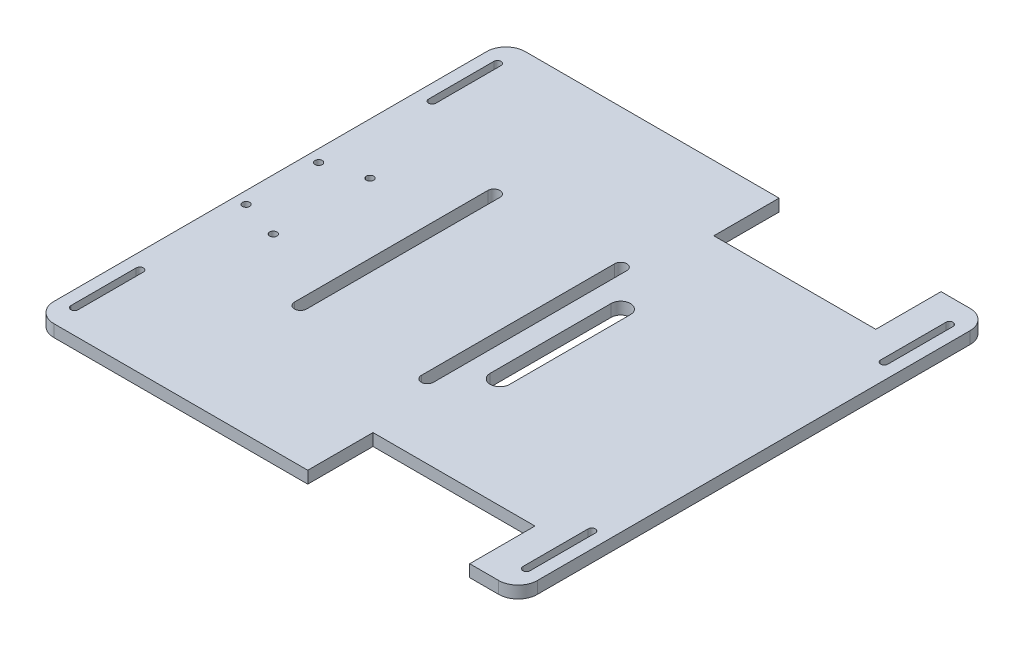
SolidWorks part; units mm, degrees
ref_plane "Front Plane" through (0, 0, 0) normal (0, 0, 1) x (1, 0, 0)
ref_plane "Top Plane" through (0, 0, 0) normal (0, 1, 0) x (1, 0, 0)
ref_plane "Right Plane" through (0, 0, 0) normal (1, 0, 0) x (0, 0, -1)
sketch "Sketch2" plane through (0, 0, 0) normal (0, 1, 0) x (1, 0, 0)
  line L1 (-100, -97.5) -> (100, -97.5)
  line L2 (-100, -97.5) -> (-100, 97.5)
  line L3 (-100, 97.5) -> (100, 97.5)
  line L4 (100, -97.5) -> (100, 97.5)
  line L5 (-100, -97.5) -> (100, 97.5) construction
  line L6 (-100, 97.5) -> (100, -97.5) construction
  point P0 (0, 0)
  dimension "D1" = 200
  dimension "D2" = 195
extrude "Boss-Extrude1" add sketch "Sketch2" along normal blind 5
sketch "Sketch3" plane through (0, 5, 0) normal (0, 1, 0) x (1, 0, 0)
  line L0 (-100, 0) -> (100, 0) construction
  line L1 (-100, 97.5) -> (-100, -97.5) construction
  line L2 (100, -97.5) -> (100, 97.5) construction
  line L3 (0, -97.5) -> (0, 97.5) construction
  line L4 (-100, -97.5) -> (100, -97.5) construction
  line L5 (100, 97.5) -> (-100, 97.5) construction
  line L6 (-93.5, -87.5) -> (-93.5, -60.5) construction
  line L7 (-95, -87.5) -> (-95, -60.5)
  line L8 (-92, -87.5) -> (-92, -60.5)
  line L9 (-93.5, 87.5) -> (-93.5, 60.5) construction
  line L10 (-95, 87.5) -> (-95, 60.5)
  line L11 (-92, 87.5) -> (-92, 60.5)
  line L12 (93.5, 87.5) -> (93.5, 60.5) construction
  line L13 (95, 87.5) -> (95, 60.5)
  line L14 (92, 87.5) -> (92, 60.5)
  line L15 (93.5, -87.5) -> (93.5, -60.5) construction
  line L16 (95, -87.5) -> (95, -60.5)
  line L17 (92, -87.5) -> (92, -60.5)
  arc A0 (-95, -87.5) -> (-92, -87.5) centre (-93.5, -87.5) ccw
  arc A1 (-92, -60.5) -> (-95, -60.5) centre (-93.5, -60.5) ccw
  arc A2 (-95, 87.5) -> (-92, 87.5) centre (-93.5, 87.5) cw
  arc A3 (-92, 60.5) -> (-95, 60.5) centre (-93.5, 60.5) cw
  arc A4 (95, 87.5) -> (92, 87.5) centre (93.5, 87.5) ccw
  arc A5 (92, 60.5) -> (95, 60.5) centre (93.5, 60.5) ccw
  arc A6 (95, -87.5) -> (92, -87.5) centre (93.5, -87.5) cw
  arc A7 (92, -60.5) -> (95, -60.5) centre (93.5, -60.5) cw
  point P14 (-93.5, -74)
  point P21 (-93.5, 74)
  point P28 (93.5, 74)
  point P35 (93.5, -74)
  dimension "D2" = 1.5
  dimension "D3" = 5
  dimension "D4" = 10
  dimension "D1" = 27
extrude "Cut-Extrude1" cut sketch "Sketch3" against normal through all
sketch "Sketch4" plane through (0, 0, 0) normal (0, -1, 0) x (1, 0, 0)
  line L0 (-100, 0) -> (100, 0) construction
  line L1 (-100, -97.5) -> (-100, 97.5) construction
  line L2 (100, 97.5) -> (100, -97.5) construction
  line L3 (100, -97.5) -> (-100, -97.5) construction
  line L4 (13, -97.5) -> (80, -97.5)
  line L5 (13, -97.5) -> (13, -70.5)
  line L6 (13, -70.5) -> (80, -70.5)
  line L7 (80, -97.5) -> (80, -70.5)
  line L8 (80, 97.5) -> (80, 70.5)
  line L9 (13, 97.5) -> (80, 97.5)
  line L10 (13, 70.5) -> (80, 70.5)
  line L11 (13, 97.5) -> (13, 70.5)
  line L12 (-47.5, 40) -> (-47.5, -40) construction
  line L13 (-45, 40) -> (-45, -40)
  line L14 (-50, 40) -> (-50, -40)
  line L15 (20, 25) -> (20, -25) construction
  line L16 (24, 25) -> (24, -25)
  line L17 (16, 25) -> (16, -25)
  line L18 (100, 97.5) -> (100, -97.5) construction
  line L19 (-100, -97.5) -> (-100, 97.5) construction
  line L20 (5, 40) -> (5, -40) construction
  line L21 (7.5, 40) -> (7.5, -40)
  line L22 (2.5, 40) -> (2.5, -40)
  arc A0 (-45, 40) -> (-50, 40) centre (-47.5, 40) ccw
  arc A1 (-50, -40) -> (-45, -40) centre (-47.5, -40) ccw
  arc A2 (24, 25) -> (16, 25) centre (20, 25) ccw
  arc A3 (16, -25) -> (24, -25) centre (20, -25) ccw
  arc A4 (7.5, 40) -> (2.5, 40) centre (5, 40) ccw
  arc A5 (2.5, -40) -> (7.5, -40) centre (5, -40) ccw
  point P18 (-47.5, 0)
  point P25 (20, 0)
  point P36 (5, 0)
  dimension "D5" = 2.5
  dimension "D8" = 4
  dimension "D11" = 2.5
  dimension "D1" = 27
  dimension "D2" = 67
  dimension "D3" = 20
  dimension "D4" = 80
  dimension "D6" = 55
  dimension "D7" = 50
  dimension "D9" = 80
  dimension "D10" = 80
  dimension "D12" = 50
extrude "Cut-Extrude2" cut sketch "Sketch4" against normal through all
sketch "Sketch8" plane through (0, 5, 0) normal (0, 1, 0) x (1, 0, 0)
  line L0 (-100, 0) -> (100, 0) construction
  line L1 (-100, 97.5) -> (-100, -97.5) construction
  line L2 (100, -97.5) -> (100, 97.5) construction
  line L3 (-78.75, -25) -> (-78.75, 25) construction
  line L4 (-95, -25) -> (-62.5, -25)
  line L5 (-95, -25) -> (-95, 25)
  line L6 (-95, 25) -> (-62.5, 25)
  line L7 (-62.5, -25) -> (-62.5, 25)
  line L8 (-95, -25) -> (-62.5, 25) construction
  line L9 (-95, 25) -> (-62.5, -25) construction
  circle A0 centre (-78.75, -19.995) radius 1.5
  circle A1 centre (-78.75, 19.995) radius 1.5
  point P6 (-78.75, 0)
  dimension "D4" = 3
  dimension "D1" = 32.5
  dimension "D2" = 50
  dimension "D3" = 5
  dimension "D5" = 39.99
extrude "Cut-Extrude6" cut sketch "Sketch8" against normal through all contours A1 | A0
sketch "Sketch9" plane through (0, 5, 0) normal (0, 1, 0) x (1, 0, 0)
  line L0 (-100, 0) -> (100, 0) construction
  line L1 (-100, 97.5) -> (-100, -97.5) construction
  line L2 (100, -97.5) -> (100, 97.5) construction
  line L4 (-100, -25) -> (-90, -25)
  line L5 (-100, -25) -> (-100, 25)
  line L6 (-100, 25) -> (-90, 25)
  line L7 (-90, -25) -> (-90, 25)
  line L8 (-100, -25) -> (-90, 25) construction
  line L9 (-100, 25) -> (-90, -25) construction
  circle A0 centre (-95, 15) radius 1.5
  circle A1 centre (-95, -15) radius 1.5
  point P6 (-95, 0)
  dimension "D4" = 3
  dimension "D1" = 10
  dimension "D2" = 0
  dimension "D3" = 50
  dimension "D5" = 30
  dimension "D6" = 5
extrude "Cut-Extrude7" cut sketch "Sketch9" against normal through all contours A0 | A1
fillet "Fillet1" radius 8 4 edges at (100, 2.5, -97.5) (100, 2.5, 97.5) (-100, 2.5, -97.5) (-100, 2.5, 97.5)
